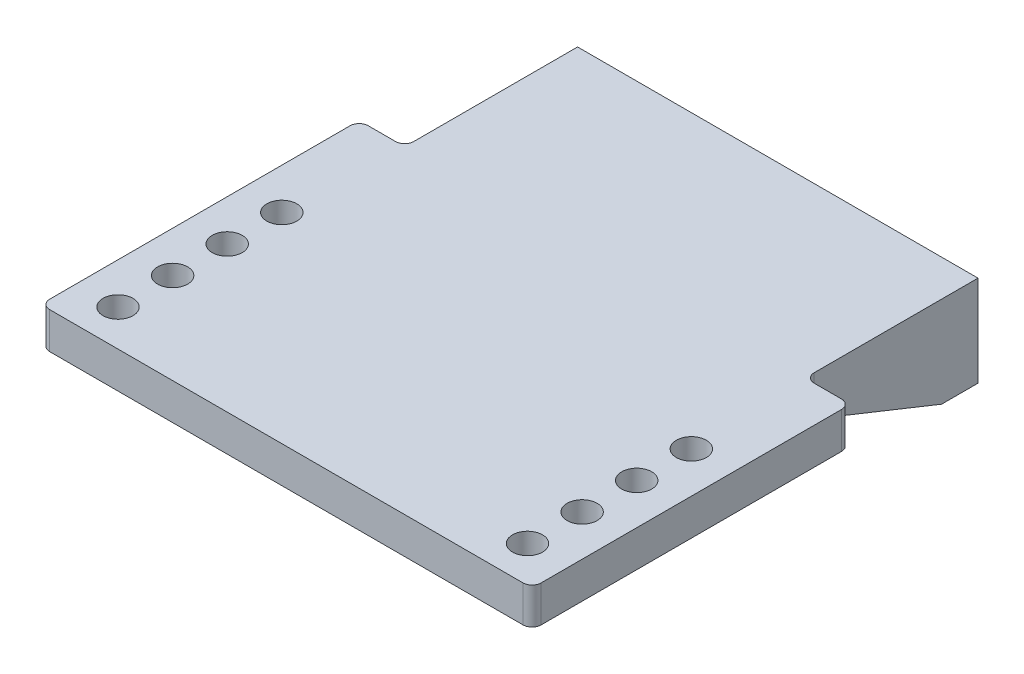
SolidWorks part; units mm, degrees
ref_plane "Front Plane" through (0, 0, 0) normal (0, 0, 1) x (1, 0, 0)
ref_plane "Top Plane" through (0, 0, 0) normal (0, 1, 0) x (1, 0, 0)
ref_plane "Right Plane" through (0, 0, 0) normal (1, 0, 0) x (0, 0, -1)
sketch "Sketch1" plane through (0, 0, 0) normal (0, 1, 0) x (1, 0, 0)
  line L0 (0, 3) -> (47.2733, 3) construction
  line L1 (0, 0) -> (44, 0)
  line L2 (0, 0) -> (0, 10)
  line L3 (0, 10) -> (44, 10)
  line L4 (44, 0) -> (44, 10)
  line L5 (22, 10) -> (22, -7.3978) construction
  circle A0 centre (38, 3) radius 1.65
  circle A1 centre (6, 3) radius 1.65
  dimension "D4" = 3.3
  dimension "D1" = 10
  dimension "D2" = 44
  dimension "D3" = 32
  dimension "D5" = 3
extrude "Boss-Extrude1" add sketch "Sketch1" along normal blind 4
sketch "Sketch2" plane through (0, 4, 0) normal (0, 1, 0) x (1, 0, 0)
  line L0 (44, 0) -> (44, 10) construction
  line L1 (0, 10) -> (44, 10)
  line L2 (0, 10) -> (0, 6)
  line L3 (0, 6) -> (44, 6)
  line L4 (44, 10) -> (44, 6)
  dimension "D1" = 4
extrude "Boss-Extrude2" add sketch "Sketch2" along normal blind 50
sketch "Sketch5" plane through (44, 0, 0) normal (1, 0, 0) x (0, 0, -1)
  line L0 (6, 19) -> (0, 4)
  line L1 (6, 54) -> (6, 4) construction
  dimension "D1" = 15
rib "Rib6" sketch "Sketch5" sketch "Sketch5" thickness 3 extrusion direction parallel to sketch draft on no parameters "D1"=3
pattern_linear "LPattern1" count 3 spacing 20.5 along (-1, 0, 0) of "Rib6"
sketch "Sketch7" plane through (44, 0, 0) normal (1, 0, 0) x (0, 0, -1)
  line L1 (6, 19) -> (10, 19)
  line L2 (6, 19) -> (6, 54)
  line L3 (6, 54) -> (10, 54)
  line L4 (10, 19) -> (10, 54)
extrude "Boss-Extrude3" add sketch "Sketch7" along normal blind 5
sketch "Sketch8" plane through (0, 0, 0) normal (-1, 0, 0) x (0, 0, 1)
  line L1 (-6, 19) -> (-10, 19)
  line L2 (-6, 19) -> (-6, 54)
  line L3 (-6, 54) -> (-10, 54)
  line L4 (-10, 19) -> (-10, 54)
extrude "Boss-Extrude4" add sketch "Sketch8" along normal blind 5
fillet "Fillet1" radius 1 6 edges at (44, 19, -8) (49, 19, -8) (49, 54, -8) (-5, 54, -8) (-5, 19, -8) (0, 19, -8)
sketch "Sketch9" plane through (0, 0, -6) normal (0, 0, 1) x (1, 0, 0)
  line L0 (-5, 32) -> (49.8185, 32) construction
  line L1 (-5, 20) -> (-5, 53) construction
  line L2 (-1, 19) -> (3, 19) construction
  line L3 (22, 54) -> (22, -2.2316) construction
  line L4 (-4, 54) -> (48, 54) construction
  circle A0 centre (-0.5, 32) radius 1.65
  circle A1 centre (44.5, 32) radius 1.65
  dimension "D2" = 3.3
  dimension "D1" = 13
  dimension "D3" = 45
extrude "Cut-Extrude1" cut sketch "Sketch9" against normal through all
pattern_linear "LPattern2" count 4 spacing 6 along (0, 1, 0) of "Cut-Extrude1"
move or copy body "Body-Move/Copy1" bodies to move or copy 107 copy no rotation origin (0, 27, -5) rotation axis (1, 0, 0) rotation angle 90
